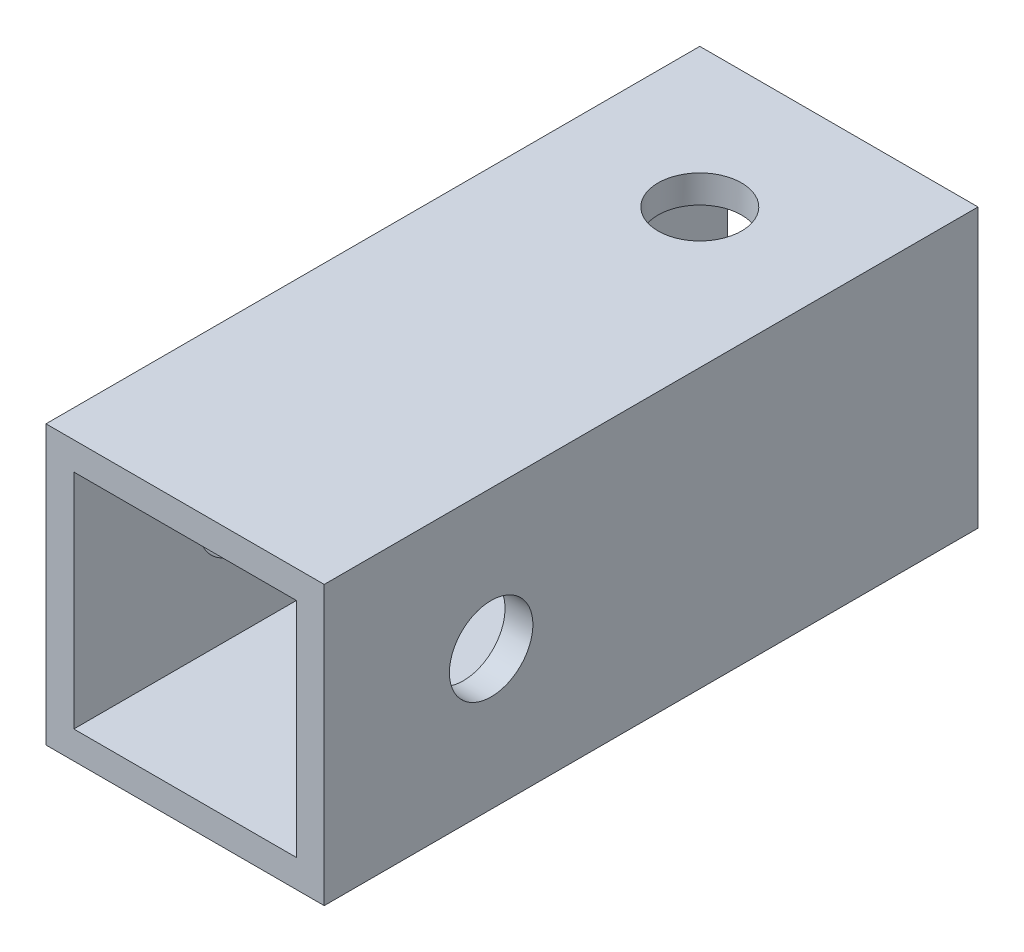
SolidWorks part; units mm, degrees
material "1060 合金"
ref_plane "正面" through (0, 0, 0) normal (0, 0, 1) x (1, 0, 0)
ref_plane "平面" through (0, 0, 0) normal (0, 1, 0) x (1, 0, 0)
ref_plane "右側面" through (0, 0, 0) normal (1, 0, 0) x (0, 0, -1)
sketch "ｽｹｯﾁ1" plane through (0, 0, 0) normal (0, 0, 1) x (1, 0, 0)
  line L1 (-5, -5) -> (5, -5)
  line L2 (-5, -5) -> (-5, 5)
  line L3 (-5, 5) -> (5, 5)
  line L4 (5, -5) -> (5, 5)
  line L5 (-5, -5) -> (5, 5) construction
  line L6 (-5, 5) -> (5, -5) construction
  point P0 (0, 0)
  dimension "D1" = 10
extrude "押し出し-薄板1" add sketch "ｽｹｯﾁ1" along normal blind 23.5 thin thin type one direction reverse wall 1
sketch "ｽｹｯﾁ2" plane through (0, 5, 0) normal (0, 1, 0) x (1, 0, 0)
  line L0 (0, 0) -> (0, -23.5) construction
  line L1 (5, 0) -> (-5, 0) construction
  line L2 (5, -23.5) -> (-5, -23.5) construction
  circle A0 centre (0, -5) radius 1.5
  dimension "D1" = 5
  dimension "D2" = 3
extrude "ｶｯﾄ - 押し出し1" cut sketch "ｽｹｯﾁ2" against normal through all
sketch "ｽｹｯﾁ3" plane through (-5, 0, 0) normal (-1, 0, 0) x (0, 0, 1)
  line L0 (0, 0) -> (23.5, 0) construction
  line L1 (23.5, 5) -> (23.5, -5) construction
  line L2 (0, 5) -> (0, -5) construction
  circle A0 centre (17.5, 0) radius 1.5
  dimension "D1" = 17.5
  dimension "D2" = 3
extrude "ｶｯﾄ - 押し出し2" cut sketch "ｽｹｯﾁ3" against normal through all
